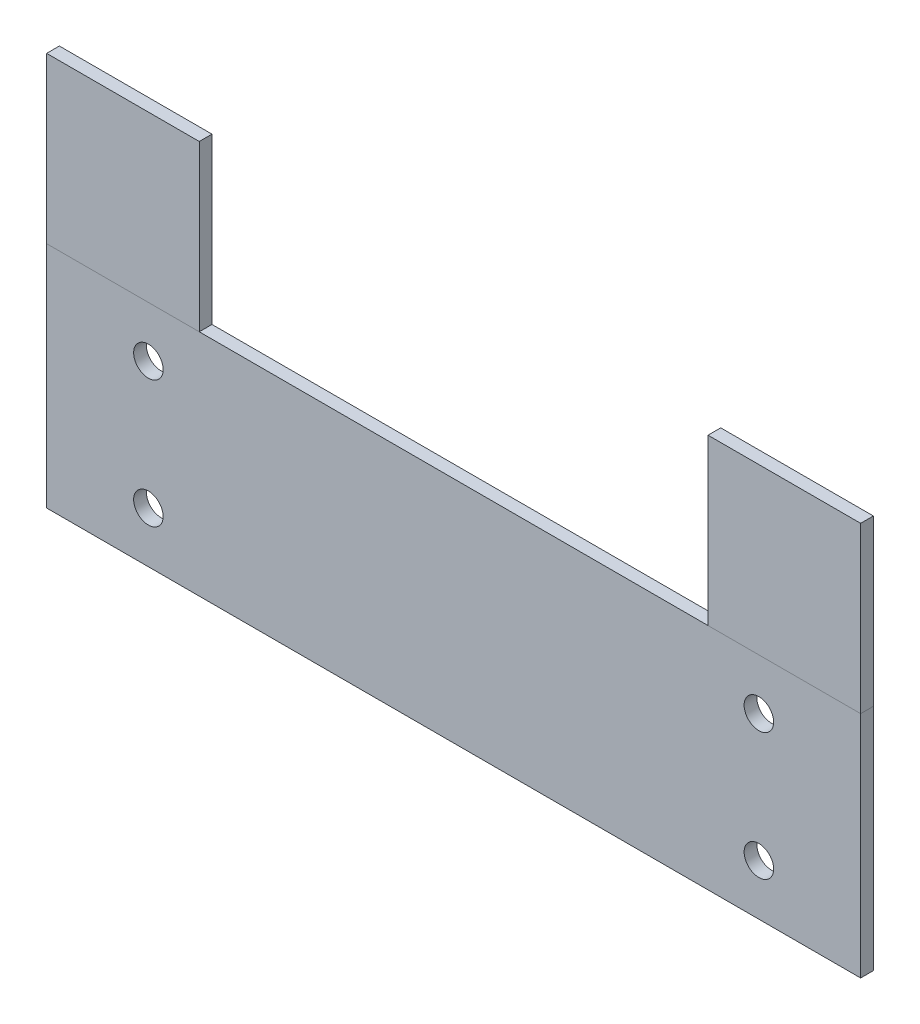
SolidWorks part; units mm, degrees
ref_plane "Front Plane" through (0, 0, 0) normal (0, 0, 1) x (1, 0, 0)
ref_plane "Top Plane" through (0, 0, 0) normal (0, 1, 0) x (1, 0, 0)
ref_plane "Right Plane" through (0, 0, 0) normal (1, 0, 0) x (0, 0, -1)
sketch "Sketch1" plane through (0, 0, 0) normal (0, 0, 1) x (1, 0, 0)
  line L1 (-50.8, 14.2875) -> (50.8, 14.2875)
  line L2 (-50.8, 14.2875) -> (-50.8, -14.2875)
  line L3 (-50.8, -14.2875) -> (50.8, -14.2875)
  line L4 (50.8, 14.2875) -> (50.8, -14.2875)
  line L5 (-50.8, 14.2875) -> (50.8, -14.2875) construction
  line L6 (-50.8, -14.2875) -> (50.8, 14.2875) construction
  point P0 (0, 0)
  dimension "D1" = 28.575
  dimension "D2" = 101.6
extrude "Boss-Extrude1" add sketch "Sketch1" along normal blind 1.5875
sketch "Sketch2" plane through (0, 0, 1.5875) normal (0, 0, 1) x (1, 0, 0)
  line L1 (38.1, -7.9375) -> (-38.1, -7.9375) construction
  line L2 (38.1, -7.9375) -> (38.1, 7.9375) construction
  line L3 (38.1, 7.9375) -> (-38.1, 7.9375) construction
  line L4 (-38.1, -7.9375) -> (-38.1, 7.9375) construction
  line L5 (38.1, -7.9375) -> (-38.1, 7.9375) construction
  line L6 (38.1, 7.9375) -> (-38.1, -7.9375) construction
  circle A0 centre (-38.1, 7.9375) radius 1.8415
  circle A1 centre (-38.1, -7.9375) radius 1.8415
  point P0 (0, 0)
  dimension "D1" = 3.683
  dimension "D4" = 3.683
  dimension "D2" = 76.2
  dimension "D3" = 15.875
extrude "Cut-Extrude1" cut sketch "Sketch2" against normal through all
sketch "Sketch3" plane through (0, 0, 1.5875) normal (0, 0, 1) x (1, 0, 0)
  line L1 (-50.8, 14.2875) -> (-31.75, 14.2875)
  line L2 (-50.8, 14.2875) -> (-50.8, 34.8615)
  line L3 (-50.8, 34.8615) -> (-31.75, 34.8615)
  line L4 (-31.75, 14.2875) -> (-31.75, 34.8615)
  line L5 (50.8, 14.2875) -> (31.75, 14.2875)
  line L6 (50.8, 14.2875) -> (50.8, 34.8615)
  line L7 (50.8, 34.8615) -> (31.75, 34.8615)
  line L8 (31.75, 14.2875) -> (31.75, 34.8615)
  dimension "D1" = 20.574
  dimension "D2" = 19.05
  dimension "D3" = 20.574
  dimension "D4" = 19.05
extrude "Boss-Extrude2" add sketch "Sketch3" against normal blind 1.5875 separate body
mirror "Mirror1" about plane through (0, 0, 0) normal (1, 0, 0) of "Cut-Extrude1"
